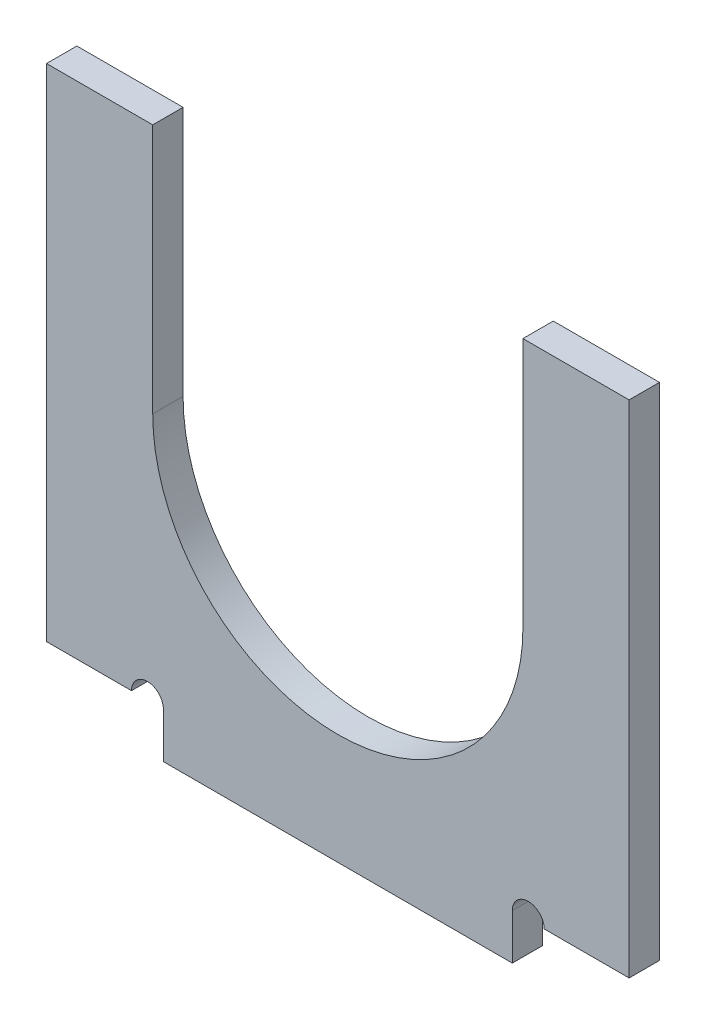
SolidWorks part; units mm, degrees
material "Thornel Mat VMA"
ref_plane "前视基准面" through (0, 0, 0) normal (0, 0, 1) x (1, 0, 0)
ref_plane "上视基准面" through (0, 0, 0) normal (0, 1, 0) x (1, 0, 0)
ref_plane "右视基准面" through (0, 0, 0) normal (1, 0, 0) x (0, 0, -1)
other "Configuration Table"
sketch "草图1" plane through (0, 0, 0) normal (0, 0, 1) x (1, 0, 0)
  line L1 (-19.2, -15) -> (19.2, -15)
  line L2 (-19.2, -15) -> (-19.2, 15)
  line L3 (-19.2, 15) -> (19.2, 15)
  line L4 (19.2, -15) -> (19.2, 15)
  line L5 (-19.2, -15) -> (19.2, 15) construction
  line L6 (-19.2, 15) -> (19.2, -15) construction
  point P0 (0, 0)
  dimension "D1" = 30
  dimension "D2" = 38.4
extrude "凸台-拉伸1" add sketch "草图1" along normal blind 2
sketch "草图2" plane through (0, 0, 0) normal (0, 0, -1) x (-1, 0, 0)
  line L0 (-12.2, 1.5) -> (-12.2, 15)
  line L1 (-19.2, 15) -> (19.2, 15) construction
  line L2 (-12.2, 15) -> (12.2, 15)
  line L3 (12.2, 15) -> (12.2, 1.5)
  circle A0 centre (0, 1.5) radius 12.2 construction
  arc A1 (-12.2, 1.5) -> (12.2, 1.5) centre (0, 1.5) ccw
extrude "切除-拉伸1" cut sketch "草图2" against normal blind 2
sketch "草图3" plane through (0, 0, 0) normal (0, 0, -1) x (-1, 0, 0)
  line L0 (19.2, -15) -> (-19.2, -15) construction
  line L1 (-11.5, -18) -> (11.5, -18)
  line L2 (-11.5, -18) -> (-11.5, -12)
  line L3 (-11.5, -12) -> (11.5, -12)
  line L4 (11.5, -18) -> (11.5, -12)
  line L5 (-11.5, -18) -> (11.5, -12) construction
  line L6 (-11.5, -12) -> (11.5, -18) construction
  point P0 (0, -15)
  point P7 (13.5801, -12)
  dimension "D1" = 3
  dimension "D2" = 23
extrude "凸台-拉伸2" add sketch "草图3" against normal up to surface (2 mm away) up to face at (0, 2.6, 2)
sketch "草图4" plane through (0, 0, 2) normal (0, 0, 1) x (1, 0, 0)
  line L0 (11.5, -15) -> (19.2, -15) construction
  line L1 (-19.2, -15) -> (-11.5, -15) construction
  circle A0 centre (12.55, -15) radius 1.05
  circle A1 centre (-12.55, -15) radius 1.05
  dimension "D1" = 2.1
extrude "切除-拉伸2" cut sketch "草图4" against normal up to surface (2 mm away) up to face at (0, -3.7667, 0)
sketch "草图5" plane through (0, 0, 0) normal (0, 0, -1) x (-1, 0, 0)
  line L0 (19.2, 15) -> (19.2, -15) construction
  line L1 (-19.2, 15) -> (-12.2, 15)
  line L2 (-19.2, 15) -> (-19.2, 18)
  line L3 (-19.2, 18) -> (-12.2, 18)
  line L4 (-12.2, 15) -> (-12.2, 18)
  line L5 (12.2, 15) -> (19.2, 15)
  line L6 (12.2, 15) -> (12.2, 18)
  line L7 (12.2, 18) -> (19.2, 18)
  line L8 (19.2, 15) -> (19.2, 18)
  line L9 (-12.2, 15) -> (-12.2, 1.5) construction
  dimension "D1" = 3
extrude "凸台-拉伸3" add sketch "草图5" against normal up to surface (2 mm away) up to face at (0, -5.2214, 2)
